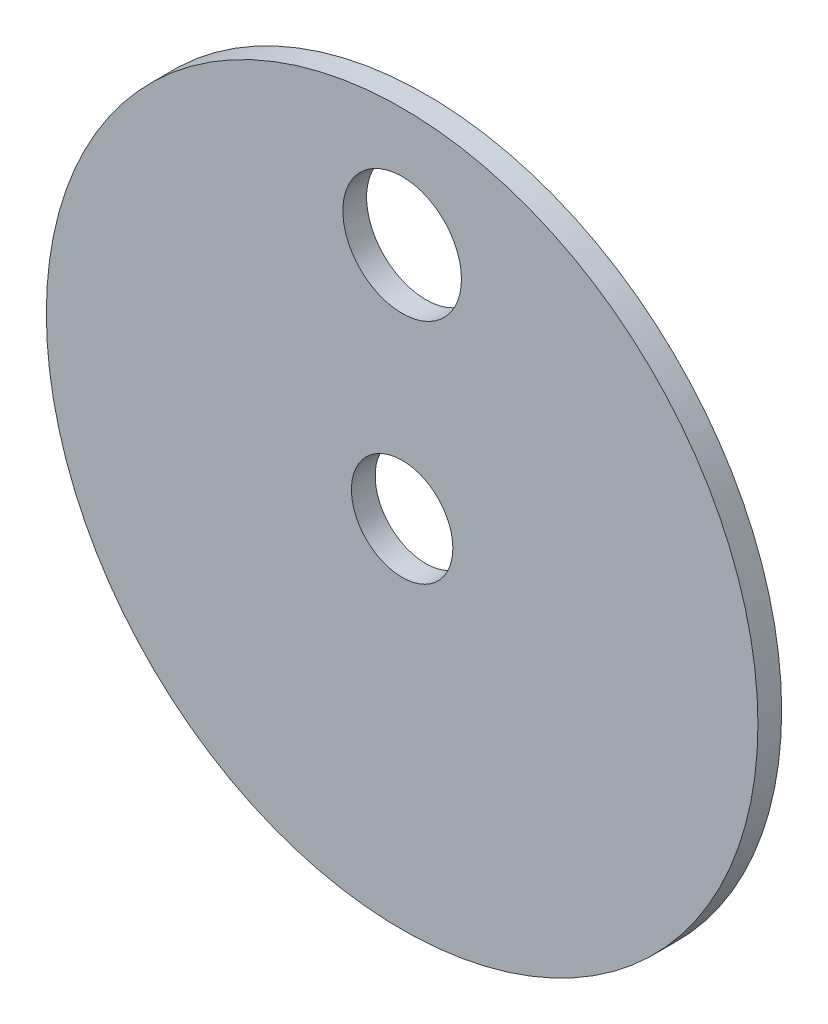
SolidWorks part; units mm, degrees
ref_plane "Front Plane" through (0, 0, 0) normal (0, 0, 1) x (1, 0, 0)
ref_plane "Top Plane" through (0, 0, 0) normal (0, 1, 0) x (1, 0, 0)
ref_plane "Right Plane" through (0, 0, 0) normal (1, 0, 0) x (0, 0, -1)
sketch "Sketch1" plane through (0, 0, 0) normal (0, 0, 1) x (1, 0, 0)
  circle A0 centre (0, 0) radius 150
  dimension "D1" = 300
extrude "Boss-Extrude1" add sketch "Sketch1" along normal blind 10
sketch "Sketch2" plane through (0, 0, 10) normal (0, 0, 1) x (1, 0, 0)
  circle A0 centre (0, 0) radius 21.3762
  circle A1 centre (0, 100) radius 25
  dimension "D1" = 50
  dimension "D2" = 100
extrude "Cut-Extrude1" cut sketch "Sketch2" against normal blind 10
